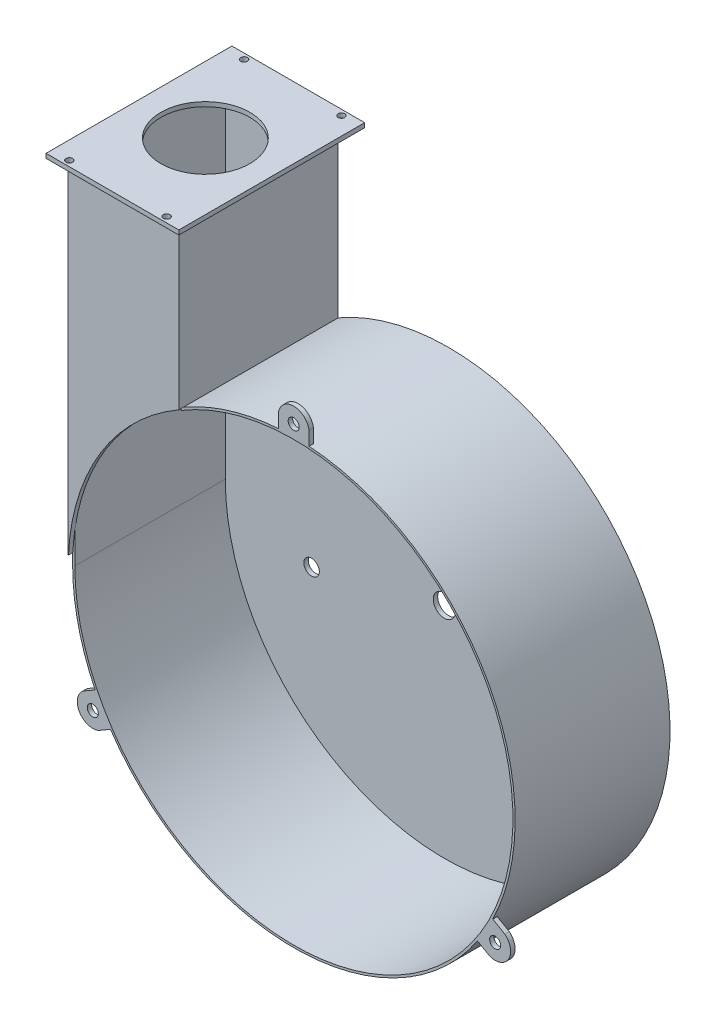
SolidWorks part; units mm, degrees
ref_plane "Ön Düzlem" through (0, 0, 0) normal (0, 0, 1) x (1, 0, 0)
ref_plane "Üst Düzlem" through (0, 0, 0) normal (0, 1, 0) x (1, 0, 0)
ref_plane "Sağ Düzlem" through (0, 0, 0) normal (1, 0, 0) x (0, 0, -1)
sketch "Çizim1" plane through (0, 0, 0) normal (0, 0, 1) x (1, 0, 0)
  line L2 (-100, 0) -> (-100, 160)
  line L3 (-100, 160) -> (-50, 160)
  line L4 (-50, 86.6025) -> (-50, 160)
  arc A0 (-100, 0) -> (-50, 86.6025) centre (0, 0) ccw
  circle A1 centre (-60, -15) radius 3.5
  circle A2 centre (60, -15) radius 3.5
  circle A3 centre (0, 0) radius 5
  dimension "D1" = 100
  dimension "D6" = 7
  dimension "D7" = 10
  dimension "D2" = 160
  dimension "D3" = 50
  dimension "D4" = 15
  dimension "D5" = 120
  dimension "D8" = 60
extrude "Yükseklik-Ekstrüzyon1" add sketch "Çizim1" along normal blind 2
sketch "Çizim2" plane through (0, 0, 2) normal (0, 0, 1) x (1, 0, 0)
  line L0 (-50, 86.6025) -> (-50, 160) construction
  line L1 (-100, 160) -> (-100, 0) construction
  line L3 (-50, 86.6025) -> (-50, 160)
  line L4 (-100, 160) -> (-100, 0)
  line L6 (-99, 159) -> (-99, 0)
  line L7 (-51, 84.8528) -> (-51, 159)
  line L9 (-50, 160) -> (-100, 160) construction
  line L10 (-51, 159) -> (-99, 159) construction
  line L11 (-99, 159) -> (-99, 160)
  line L12 (-50, 160) -> (-100, 160) construction
  line L13 (-99, 160) -> (-100, 160)
  line L14 (-51, 159) -> (-51, 160)
  line L15 (-51, 160) -> (-50, 160)
  arc A0 (-100, 0) -> (-50, 86.6025) centre (0, 0) ccw construction
  arc A1 (-100, 0) -> (-50, 86.6025) centre (0, 0) ccw
  arc A2 (-99, 0) -> (-51, 84.8528) centre (0, 0) ccw
  dimension "D1" = 1
extrude "Yükseklik-Ekstrüzyon3" add sketch "Çizim2" along normal blind 68
sketch "Çizim4" plane through (0, 0, 70) normal (0, 0, 1) x (1, 0, 0)
  line L0 (-50, 86.6025) -> (-50, 160) construction
  line L1 (-100, 160) -> (-50, 160)
  line L2 (-100, 160) -> (-100, 4.7707)
  line L3 (-100, 4.7707) -> (-99.8861, 4.7707)
  line L4 (-50, 160) -> (-50, 86.6025)
  arc A0 (-50, 86.6025) -> (-99.8861, 4.7707) centre (0, 0) ccw
extrude "Yükseklik-Ekstrüzyon4" add sketch "Çizim4" along normal blind 2 contours A0 L3 L2 L1 L4
sketch "Çizim6" plane through (0, 0, 70) normal (0, 0, 1) x (1, 0, 0)
  line L0 (95.3333, -46.9578) -> (89.8901, -43.8152)
  line L1 (-7, 106.0399) -> (-7, 99.7547)
  line L2 (6.8446, 106.0399) -> (6.8446, 99.7655)
  line L3 (88.411, -58.9476) -> (82.9771, -55.8104)
  line L4 (-88.3333, -59.0821) -> (-82.8901, -55.9395)
  line L5 (-95.2556, -47.0923) -> (-89.8218, -43.9551)
  arc A0 (-100, 0) -> (-50, 86.6025) centre (0, 0) ccw construction
  arc A1 (-100, 0) -> (-50, 86.6025) centre (0, 0) ccw
  arc A2 (6.8446, 106.0399) -> (-7, 106.0399) centre (-0.0777, 105) ccw
  circle A3 centre (-0.0777, 105) radius 2.5
  arc A4 (88.411, -58.9476) -> (95.3333, -46.9578) centre (90.9715, -52.4327) ccw
  circle A5 centre (90.9715, -52.4327) radius 2.5
  arc A6 (-95.2556, -47.0923) -> (-88.3333, -59.0821) centre (-90.8938, -52.5673) ccw
  circle A7 centre (-90.8938, -52.5673) radius 2.5
  point P9 (-7, 102.8973)
  point P24 (0, 0)
  arc M7 (-100, 0) -> (-50, 86.6025) centre (0, 0) ccw
  dimension "D1" = 7
  dimension "D4" = 5
  dimension "D2" = 105
  dimension "D3" = 7
  dimension "D5" = 3
extrude "Yükseklik-Ekstrüzyon6" add sketch "Çizim6" against normal blind 2 contours L2 A2 L1 A3 M7 | L5 A6 L4 A7 M7 | L3 A4 L0 A5 M7
sketch "Çizim8" plane through (0, 160, 0) normal (0, 1, 0) x (1, 0, 0)
  line L1 (-105, 7) -> (-45, 7)
  line L2 (-105, 7) -> (-105, -77)
  line L3 (-105, -77) -> (-45, -77)
  line L4 (-45, 7) -> (-45, -77)
  line L5 (-50, 0) -> (-100, 0) construction
  line L6 (-100, -72) -> (-100, 0) construction
  circle A0 centre (-75, -35) radius 20.1221
  circle A1 centre (-97, 4.5) radius 1.5
  circle A2 centre (-53, 4.5) radius 1.5
  circle A3 centre (-53, -74.5) radius 1.5
  circle A4 centre (-97, -74.5) radius 1.5
  dimension "D8" = 3
  dimension "D1" = 60
  dimension "D2" = 84
  dimension "D3" = 30
  dimension "D4" = 42
  dimension "D5" = 7
  dimension "D6" = 5
  dimension "D7" = 39.5
  dimension "D9" = 22
  dimension "D10" = 2
  dimension "D11" = 2
extrude "Yükseklik-Ekstrüzyon7" add sketch "Çizim8" along normal blind 2
